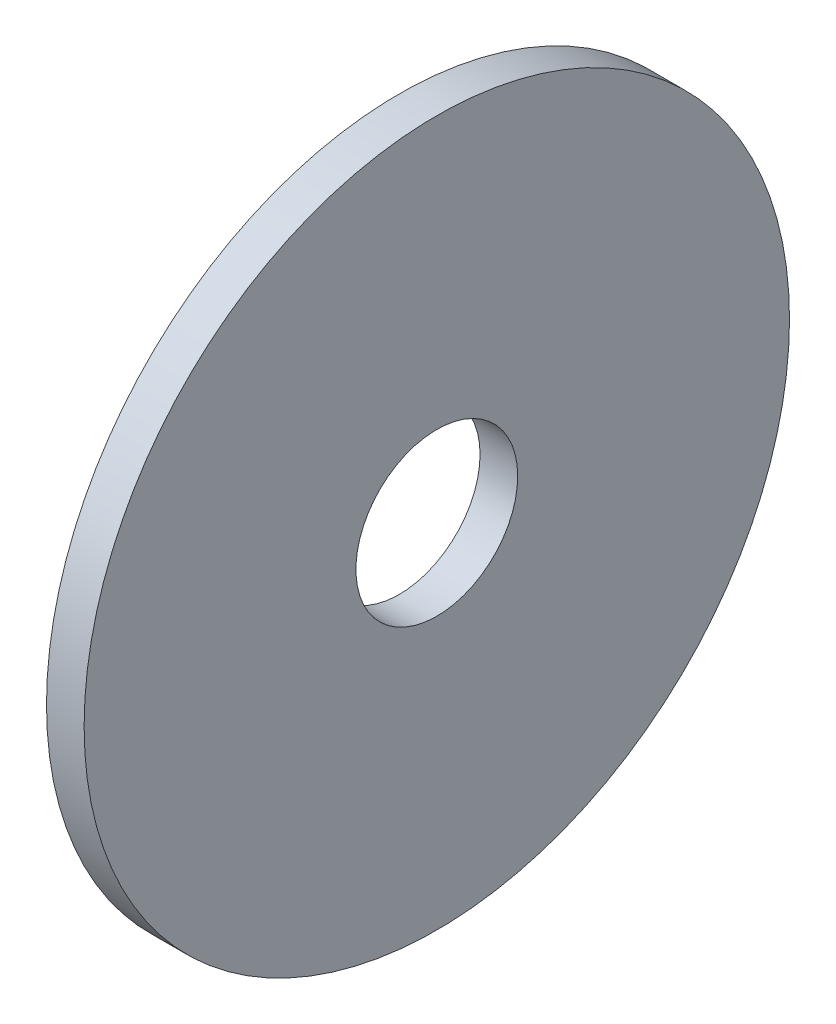
SolidWorks part; units mm, degrees
material "AISI 304"
ref_plane "Front Plane" through (0, 0, 0) normal (0, 0, 1) x (1, 0, 0)
ref_plane "Top Plane" through (0, 0, 0) normal (0, 1, 0) x (1, 0, 0)
ref_plane "Right Plane" through (0, 0, 0) normal (1, 0, 0) x (0, 0, -1)
sketch "Sketch1" plane through (0, 0, 0) normal (1, 0, 0) x (0, 0, -1)
  circle A0 centre (0, 0) radius 19.05
  circle A1 centre (0, 0) radius 4.3688
  dimension "OD" = 38.1
  dimension "ID" = 8.7376
extrude "Boss-Extrude1" add sketch "Sketch1" along normal blind 2.032
